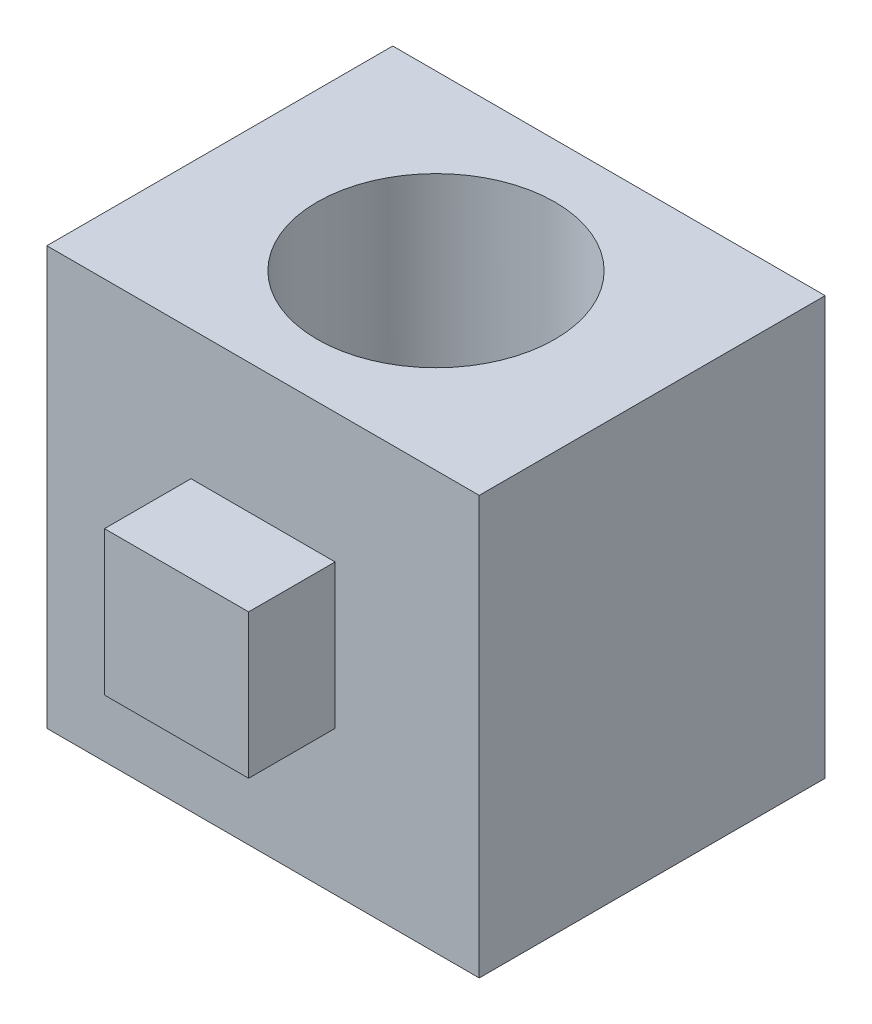
SolidWorks part; units mm, degrees
material "Gray Cast Iron"
ref_plane "Front Plane" through (0, 0, 0) normal (0, 0, 1) x (1, 0, 0)
ref_plane "Top Plane" through (0, 0, 0) normal (0, 1, 0) x (1, 0, 0)
ref_plane "Right Plane" through (0, 0, 0) normal (1, 0, 0) x (0, 0, -1)
sketch "Sketch1" plane through (0, 0, 0) normal (0, 0, 1) x (1, 0, 0)
  line L0 (-15, 0) -> (15, 0)
  line L1 (15, 0) -> (15, 29)
  line L2 (15, 29) -> (-15, 29)
  line L3 (-15, 29) -> (-15, 0)
  dimension "D1" = 30
  dimension "D2" = 29
  dimension "D3" = 15
extrude "Boss-Extrude1" add sketch "Sketch1" along normal mid plane 24
sketch "Sketch2" plane through (0, 0, 0) normal (0, 1, 0) x (1, 0, 0)
  circle A0 centre (0, 0) radius 8.25
  dimension "D1" = 16.5
extrude "Cut-Extrude1" cut sketch "Sketch2" against normal mid plane 68
sketch "Sketch3" plane through (0, 0, 0) normal (0, 0, 1) x (1, 0, 0)
  line L0 (-5, 10) -> (5, 10)
  line L1 (5, 10) -> (5, 20)
  line L2 (5, 20) -> (-5, 20)
  line L3 (-5, 20) -> (-5, 10)
  dimension "D1" = 10
  dimension "D2" = 10
  dimension "D3" = 5
  dimension "D4" = 10
extrude "Boss-Extrude2" add sketch "Sketch3" along normal blind 6 from offset 12
